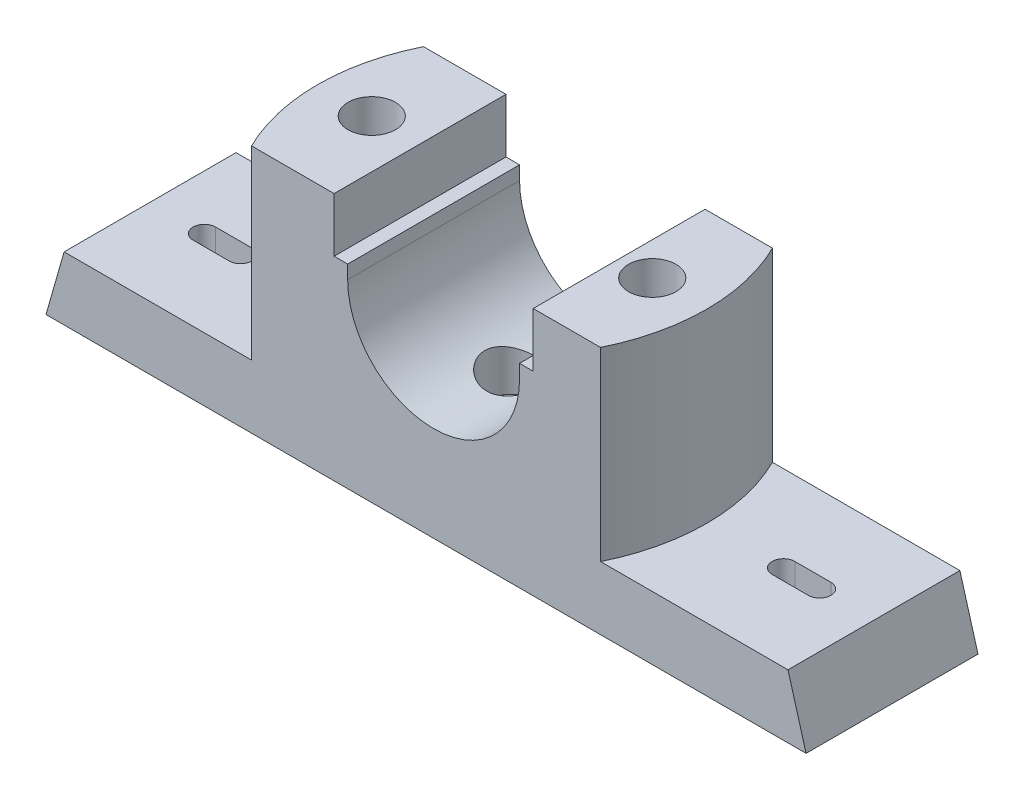
SolidWorks part; units mm, degrees
ref_plane "Front Plane" through (0, 0, 0) normal (0, 0, 1) x (1, 0, 0)
ref_plane "Top Plane" through (0, 0, 0) normal (0, 1, 0) x (1, 0, 0)
ref_plane "Right Plane" through (0, 0, 0) normal (1, 0, 0) x (0, 0, -1)
sketch "Sketch2" plane through (0, 0, 0) normal (0, 0, 1) x (1, 0, 0)
  line L0 (0, 0) -> (0, -103.9215) construction
  line L1 (0, -103.9215) -> (0, 89.3419) construction
  line L2 (0, 0) -> (141.3874, 0) construction
  line L3 (141.3874, 0) -> (-138.675, 0) construction
  line L4 (-84, 0) -> (0, 0)
  line L5 (0, 0) -> (84, 0)
  line L6 (80, 14) -> (-80, 14)
  line L7 (-80, 14) -> (-84, 0)
  line L11 (80, 14) -> (84, 0)
extrude "Boss-Extrude1" add sketch "Sketch2" along normal mid plane 38
sketch "Sketch3" plane through (0, 0, 0) normal (0, -1, 0) x (1, 0, 0)
  line L0 (0, 0) -> (0, -69.2032) construction
  line L1 (0, -69.2032) -> (0, 60.5953) construction
  line L2 (0, 0) -> (121.8702, 0) construction
  line L3 (121.8702, 0) -> (-121.4171, 0) construction
  line L4 (-76, 11) -> (-76, 0)
  line L5 (-76, 0) -> (-76, -11)
  line L6 (-76, -11) -> (-8, -11)
  line L7 (-8, -11) -> (-8, 11)
  line L8 (-8, 11) -> (-76, 11)
  line L9 (76, 0) -> (76, -11)
  line L11 (76, 11) -> (76, 0)
  line L12 (76, -11) -> (8, -11)
  line L13 (8, 11) -> (76, 11)
  line L14 (8, -11) -> (8, 11)
extrude "Cut-Extrude2" cut sketch "Sketch3" against normal blind 2
sketch "Sketch4" plane through (0, 14, 0) normal (0, 1, 0) x (1, 0, 0)
  line L0 (0, 0) -> (0, -19) construction
  line L1 (0, -74.1868) -> (0, -43) construction
  line L2 (0, 0) -> (127.3067, 0) construction
  line L3 (127.3067, 0) -> (-130.9311, 0) construction
  line L4 (-38.5746, 19) -> (38.5746, 19)
  line L5 (80, 19) -> (-80, 19) construction
  line L6 (38.5746, -19) -> (-38.5746, -19)
  line L7 (80, -19) -> (-80, -19) construction
  line L8 (0, -43) -> (0, -74.1868) construction
  line L9 (0, -19) -> (0, 58.5566) construction
  arc A0 (38.5746, -19) -> (38.5746, 19) centre (0, 0) ccw
  arc A1 (-38.5746, 19) -> (-38.5746, -19) centre (0, 0) ccw
extrude "Boss-Extrude2" add sketch "Sketch4" along normal blind 41
sketch "Sketch5" plane through (0, 0, 19) normal (0, 0, 1) x (1, 0, 0)
  line L0 (0.2337, -1.39) -> (-1.3591, -47.1398) construction
  line L1 (-1.3591, -47.1398) -> (3.5299, 93.2843) construction
  line L2 (1.6747, 39.9999) -> (109.6378, 39.9999) construction
  line L3 (109.6378, 39.9999) -> (-107.8256, 39.9999) construction
  line L4 (20.6747, 39.9999) -> (20.6747, 43)
  line L5 (-17.3253, 39.9999) -> (-17.3253, 43)
  line L6 (-17.3253, 43) -> (-20.3253, 43)
  line L7 (-20.3253, 43) -> (-20.3253, 55)
  line L8 (-38.5746, 55) -> (38.5746, 55) construction
  line L9 (20.6747, 43) -> (23.6747, 43)
  line L10 (23.6747, 43) -> (23.6747, 55)
  line L11 (-20.3253, 55) -> (23.6747, 55)
  arc A0 (-17.3253, 39.9999) -> (20.6747, 39.9999) centre (1.6747, 39.9999) ccw
extrude "Cut-Extrude3" cut sketch "Sketch5" against normal blind 62
sketch "Sketch6" plane through (0, 0, 0) normal (0, -1, 0) x (1, 0, 0)
  line L0 (0, 0) -> (0, -74.6398) construction
  line L1 (0, -74.6398) -> (0, 50.1752) construction
  line L2 (0, 0) -> (98.3116, 0) construction
  line L3 (98.3116, 0) -> (-57.5, 0) construction
  line L5 (68, 2.5) -> (60, 2.5)
  line L6 (-68, 2.5) -> (-60, 2.5)
  line L7 (68, -2.5) -> (60, -2.5)
  line L8 (-68, -2.5) -> (-60, -2.5)
  line L15 (-70.5, 0) -> (-105.3339, 0) construction
  arc A0 (-60, -2.5) -> (-60, 2.5) centre (-60, 0) ccw
  arc A1 (-68, 2.5) -> (-68, -2.5) centre (-68, 0) ccw
  circle A2 centre (-31, 0) radius 5.25
  circle A3 centre (31, 0) radius 5.25
  arc A4 (68, 2.5) -> (68, -2.5) centre (68, 0) cw
  arc A5 (60, -2.5) -> (60, 2.5) centre (60, 0) cw
extrude "Cut-Extrude4" cut sketch "Sketch6" against normal blind 72
sketch "Sketch7" plane through (0, 0, 0) normal (0, -1, 0) x (1, 0, 0)
  circle A0 centre (-31, 0) radius 10
  circle A1 centre (31, 0) radius 10
extrude "Cut-Extrude5" cut sketch "Sketch7" against normal blind 9
sketch "Sketch8" plane through (0, 55, 0) normal (0, 1, 0) x (1, 0, 0)
  line L0 (0, 0) -> (-112.4329, 0) construction
  line L1 (-112.4329, 0) -> (115.6128, 0) construction
  line L2 (0, 0) -> (0, 62.3491) construction
  line L3 (0, 62.3491) -> (0, -57.3521) construction
  circle A0 centre (0, 0) radius 6
extrude "Cut-Extrude6" cut sketch "Sketch8" against normal blind 42
